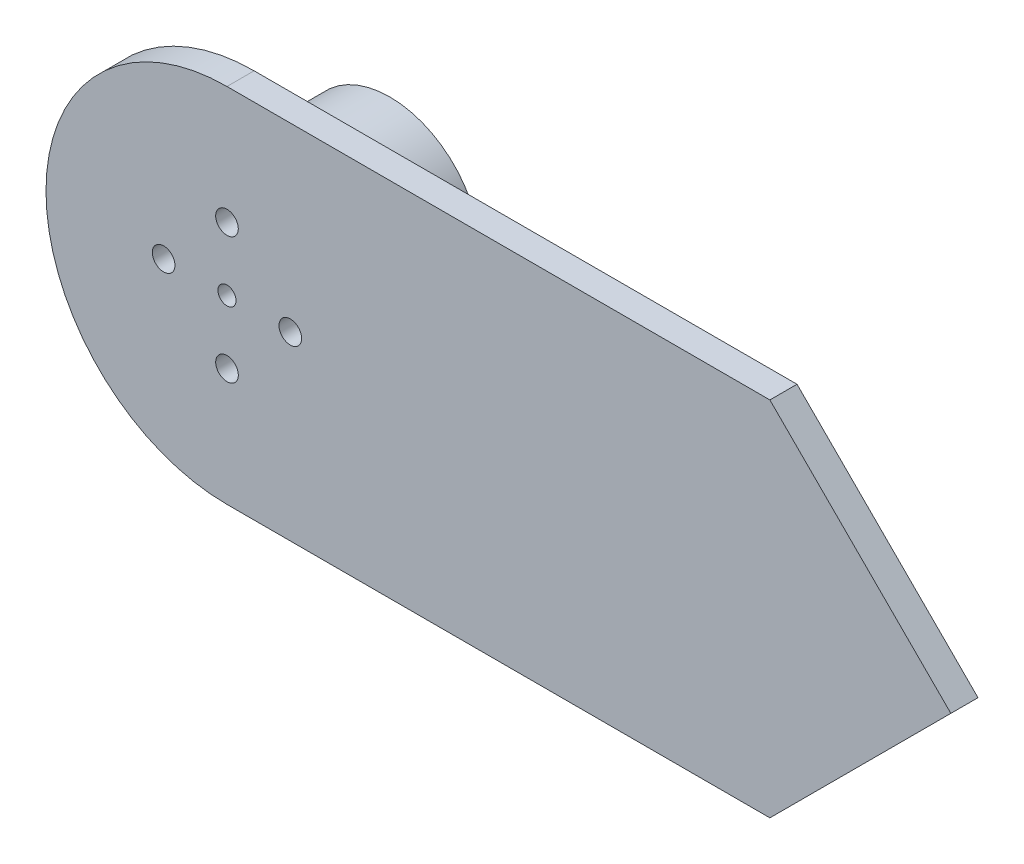
SolidWorks part; units mm, degrees
ref_plane "Front Plane" through (0, 0, 0) normal (0, 0, 1) x (1, 0, 0)
ref_plane "Top Plane" through (0, 0, 0) normal (0, 1, 0) x (1, 0, 0)
ref_plane "Right Plane" through (0, 0, 0) normal (1, 0, 0) x (0, 0, -1)
sketch "Sketch1" plane through (0, 0, 0) normal (0, 1, 0) x (1, 0, 0)
  line L0 (60, -20) -> (0, -20)
  line L2 (0, 20) -> (60, 20)
  line L3 (60, 20) -> (80, 0)
  line L4 (80, 0) -> (60, -20)
  arc A0 (0, 20) -> (0, -20) centre (0, 0) ccw
  dimension "D1" = 40
  dimension "D3" = 60
  dimension "D2" = 60
  dimension "D4" = 80
extrude "Boss-Extrude1" add sketch "Sketch1" along normal blind 3 contours L2 L3 L4 L0 A0
sketch "Sketch2" plane through (0, 3, 0) normal (0, 1, 0) x (1, 0, 0)
  circle A0 centre (0, 0) radius 1
  circle A1 centre (0, 7) radius 1.25
  circle A2 centre (0.001, 0.001) radius 1
  circle A3 centre (7.001, 0.001) radius 1.25
  circle A4 centre (0.002, 0) radius 1
  circle A5 centre (0.002, -7) radius 1.25
  circle A6 centre (0.001, -0.001) radius 1
  circle A7 centre (-6.999, -0.001) radius 1.25
  point P20 (0.001, 0)
  dimension "D1" = 2
  dimension "D2" = 2.5
  dimension "D4" = 7
  dimension "D3" = 4
extrude "Cut-Extrude1" cut sketch "Sketch2" against normal up to next contours A1 | A0 | A3 | A5 | A7
sketch "Sketch3" plane through (0, 0, 0) normal (0, -1, 0) x (1, 0, 0)
  circle A0 centre (0, 0) radius 10
  dimension "D1" = 20
extrude "Boss-Extrude2" add sketch "Sketch3" along normal blind 15
move or copy body "Body-Move/Copy2" bodies to move or copy 110 copy no rotation origin (0, 0, 0) rotation axis (1, 0, 0) rotation angle 90
move or copy body "Body-Move/Copy3" bodies to move or copy 112 copy no translate (0, 0, -3)
